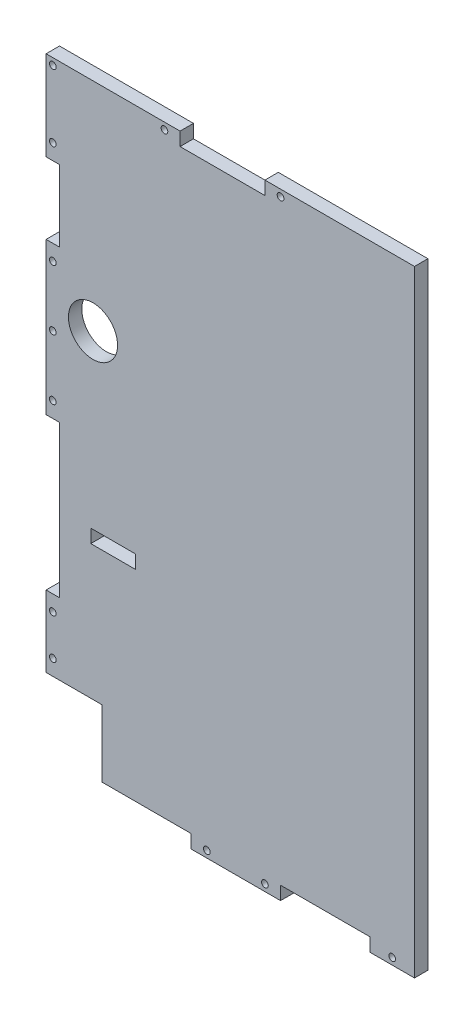
SolidWorks part; units mm, degrees
ref_plane "Plan de face" through (0, 0, 0) normal (0, 0, 1) x (1, 0, 0)
ref_plane "Plan de dessus" through (0, 0, 0) normal (0, 1, 0) x (1, 0, 0)
ref_plane "Plan de droite" through (0, 0, 0) normal (1, 0, 0) x (0, 0, -1)
sketch "Esquisse1" plane through (0, 0, 0) normal (0, 0, 1) x (1, 0, 0)
  line L1 (0, 0) -> (-165, 0)
  line L2 (0, 0) -> (0, 276)
  line L3 (0, 276) -> (-165, 276)
  line L4 (-165, 0) -> (-165, 276)
  dimension "D1" = 276
  dimension "D2" = 165
extrude "Boss.-Extru.1" add sketch "Esquisse1" along normal blind 6
sketch "Esquisse2" plane through (0, 0, 6) normal (0, 0, 1) x (1, 0, 0)
  line L0 (0, 276) -> (-165, 276) construction
  line L8 (0, 276) -> (-165, 276) construction
  line L9 (-165, 0) -> (0, 0) construction
  line L10 (-105, 276) -> (-67, 276)
  line L11 (-105, 276) -> (-105, 270)
  line L12 (-105, 270) -> (-67, 270)
  line L13 (-165, 276) -> (-165, 0) construction
  line L14 (-165, 236) -> (-159, 236)
  line L15 (-165, 236) -> (-165, 204)
  line L16 (-165, 204) -> (-159, 204)
  line L17 (-159, 236) -> (-159, 204)
  line L19 (-165, 136) -> (-159, 136)
  line L20 (-165, 136) -> (-165, 68)
  line L21 (-165, 68) -> (-159, 68)
  line L22 (-159, 136) -> (-159, 68)
  line L23 (-140, 36) -> (-140, 6)
  line L24 (-165, 0) -> (-165, 36)
  line L25 (-165, 36) -> (-140, 36)
  line L26 (-100, 0) -> (-165, 0)
  line L27 (-20, 0) -> (-60, 0)
  line L28 (-20, 0) -> (-20, 6)
  line L29 (-20, 6) -> (-60, 6)
  line L30 (-60, 0) -> (-60, 6)
  line L31 (0, 0) -> (0, 276) construction
  line L33 (-100, 0) -> (-100, 6)
  line L34 (-100, 6) -> (-140, 6)
  line L35 (-67, 276) -> (-67, 270)
  dimension "D1" = 6
  dimension "D2" = 6
  dimension "D3" = 68
  dimension "D4" = 32
  dimension "D5" = 40
  dimension "D6" = 68
  dimension "D7" = 36
  dimension "D8" = 25
  dimension "D9" = 6
  dimension "D10" = 40
  dimension "D11" = 6
  dimension "D12" = 40
  dimension "D13" = 20
  dimension "D14" = 38
  dimension "D15" = 60
  dimension "D16" = 6
extrude "exterieur" cut sketch "Esquisse2" against normal blind 10
sketch "Esquisse3" plane through (0, 0, 6) normal (0, 0, 1) x (1, 0, 0)
  line L0 (-165, 204) -> (-159, 204) construction
  line L1 (-145, 102) -> (-125, 102)
  line L2 (-145, 102) -> (-145, 96)
  line L3 (-145, 96) -> (-125, 96)
  line L4 (-125, 102) -> (-125, 96)
  line L5 (-165, 204) -> (-165, 136) construction
  line L6 (-165, 68) -> (-165, 36) construction
  line L8 (-100, 0) -> (-60, 0) construction
  circle A0 centre (-144, 178.92) radius 11
  dimension "D1" = 22
  dimension "D2" = 20
  dimension "D4" = 21
  dimension "D3" = 6
  dimension "D5" = 25.08
  dimension "D6" = 20
  dimension "D7" = 102
extrude "Enlèv. mat.-Extru.2" cut sketch "Esquisse3" against normal through all
sketch "Esquisse4" plane through (0, 0, 6) normal (0, 0, 1) x (1, 0, 0)
  line L0 (-105, 270) -> (-67, 270) construction
  line L1 (-105, 276) -> (-165, 276) construction
  line L2 (-105, 276) -> (-105, 270) construction
  line L3 (-67, 270) -> (-67, 276) construction
  line L4 (-165, 204) -> (-159, 204) construction
  line L5 (-159, 136) -> (-165, 136) construction
  line L6 (-165, 68) -> (-159, 68) construction
  line L7 (-140, 36) -> (-165, 36) construction
  line L8 (-100, 0) -> (-100, 6) construction
  line L9 (-60, 6) -> (-60, 0) construction
  line L10 (-100, 0) -> (-60, 0) construction
  line L11 (-165, 68) -> (-165, 36) construction
  line L12 (-165, 204) -> (-165, 136) construction
  line L13 (-20, 0) -> (0, 0) construction
  line L14 (-20, 0) -> (-20, 6) construction
  line L15 (-165, 276) -> (-165, 236) construction
  line L16 (-159, 236) -> (-165, 236) construction
  circle A0 centre (-60, 273) radius 1.5
  circle A1 centre (-112, 273) radius 1.5
  circle A2 centre (-162, 197) radius 1.5
  circle A3 centre (-162, 170) radius 1.5
  circle A4 centre (-162, 143) radius 1.5
  circle A5 centre (-162, 61) radius 1.5
  circle A6 centre (-162, 43) radius 1.5
  circle A7 centre (-93, 3) radius 1.5
  circle A8 centre (-67, 3) radius 1.5
  circle A9 centre (-10, 3) radius 1.5
  circle A10 centre (-162, 273) radius 1.5
  circle A11 centre (-162, 243) radius 1.5
  point P28 (-162, 204)
  point P45 (-165, 170)
  point P46 (-10, 0)
  point P49 (-20, 3)
  point P60 (-162, 236)
  dimension "D1" = 3
  dimension "D2" = 3
  dimension "D3" = 3
  dimension "D4" = 7
  dimension "D5" = 3
  dimension "D6" = 7
  dimension "D7" = 3
  dimension "D8" = 7
  dimension "D9" = 3
  dimension "D10" = 34
  dimension "D11" = 3
  dimension "D12" = 7
  dimension "D13" = 3
  dimension "D14" = 7
  dimension "D15" = 3
  dimension "D16" = 7
  dimension "D17" = 3
  dimension "D18" = 3
  dimension "D19" = 7
  dimension "D20" = 7
  dimension "D21" = 3
  dimension "D22" = 3
  dimension "D23" = 3
  dimension "D24" = 3
  dimension "D25" = 3
  dimension "D26" = 3
  dimension "D27" = 3
  dimension "D28" = 3
  dimension "D29" = 3
  dimension "D30" = 10
  dimension "D31" = 3
  dimension "D32" = 3
  dimension "D33" = 3
  dimension "D34" = 3
  dimension "D35" = 7
  dimension "D36" = 3
extrude "Enlèv. mat.-Extru.3" cut sketch "Esquisse4" against normal through all
sketch "Esquisse5" plane through (0, 0, 0) normal (0, 0, -1) x (-1, 0, 0)
  circle A0 centre (60, 273) radius 2.995
  circle A1 centre (112, 273) radius 2.995
  circle A2 centre (162, 197) radius 2.995
  circle A3 centre (162, 170) radius 2.995
  circle A4 centre (162, 143) radius 2.995
  circle A5 centre (162, 61) radius 2.995
  circle A6 centre (162, 43) radius 2.995
  circle A7 centre (93, 3) radius 2.995
  circle A8 centre (67, 3) radius 2.995
  circle A9 centre (10, 3) radius 2.995
  circle A10 centre (162, 273) radius 2.995
  circle A11 centre (162, 243) radius 2.995
  dimension "D1" = 5.99
  dimension "D2" = 5.99
  dimension "D3" = 5.99
  dimension "D4" = 5.99
  dimension "D5" = 5.99
  dimension "D6" = 5.99
  dimension "D7" = 5.99
  dimension "D8" = 5.99
  dimension "D9" = 5.99
  dimension "D10" = 5.99
  dimension "D11" = 5.99
  dimension "D12" = 5.99
extrude "Enlèv. mat.-Extru.4" cut sketch "Esquisse5" against normal blind 3
